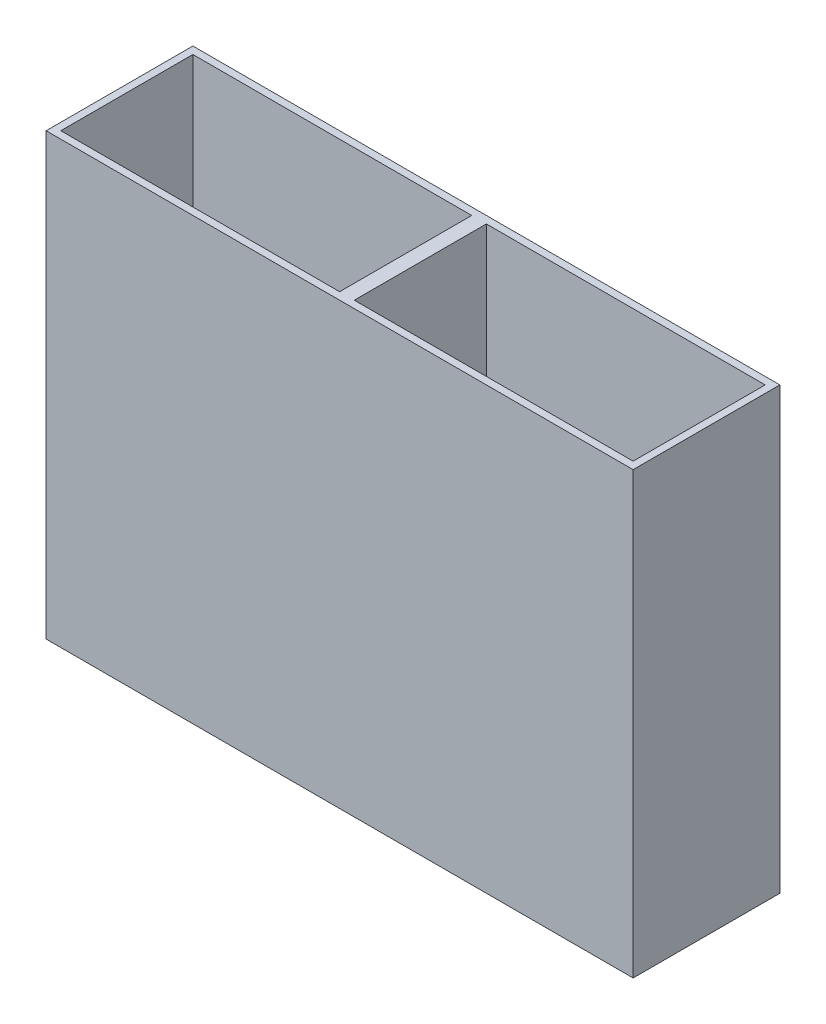
SolidWorks part; units mm, degrees
ref_plane "Front Plane" through (0, 0, 0) normal (0, 0, 1) x (1, 0, 0)
ref_plane "Top Plane" through (0, 0, 0) normal (0, 1, 0) x (1, 0, 0)
ref_plane "Right Plane" through (0, 0, 0) normal (1, 0, 0) x (0, 0, -1)
sketch "Sketch1" plane through (0, 0, 0) normal (0, 1, 0) x (1, 0, 0)
  line L1 (-254, 63.5) -> (254, 63.5)
  line L2 (-254, 63.5) -> (-254, -63.5)
  line L3 (-254, -63.5) -> (254, -63.5)
  line L4 (254, 63.5) -> (254, -63.5)
  line L5 (-254, 63.5) -> (254, -63.5) construction
  line L6 (-254, -63.5) -> (254, 63.5) construction
  point P0 (0, 0)
  dimension "D1" = 127
  dimension "D2" = 508
extrude "Boss-Extrude1" add sketch "Sketch1" along normal blind 381
sketch "Sketch2" plane through (0, 381, 0) normal (0, 1, 0) x (1, 0, 0)
  line L0 (0, 63.5) -> (0, -63.5) construction
  line L1 (254, 63.5) -> (-254, 63.5) construction
  line L2 (-254, -63.5) -> (254, -63.5) construction
  line L3 (0, 0) -> (-254, 0) construction
  line L4 (-254, 63.5) -> (-254, -63.5) construction
  line L5 (247.65, 57.15) -> (247.65, -57.15)
  line L6 (-247.65, 57.15) -> (-6.35, 57.15)
  line L7 (-247.65, 57.15) -> (-247.65, -57.15)
  line L8 (-247.65, -57.15) -> (-6.35, -57.15)
  line L9 (-6.35, 57.15) -> (-6.35, -57.15)
  line L10 (-247.65, 57.15) -> (-6.35, -57.15) construction
  line L11 (-247.65, -57.15) -> (-6.35, 57.15) construction
  line L12 (247.65, -57.15) -> (6.35, -57.15)
  line L13 (6.35, 57.15) -> (6.35, -57.15)
  line L14 (247.65, 57.15) -> (6.35, 57.15)
  point P11 (-127, 0)
  dimension "D1" = 241.3
  dimension "D2" = 114.3
extrude "Cut-Extrude1" cut sketch "Sketch2" against normal blind 379.73
